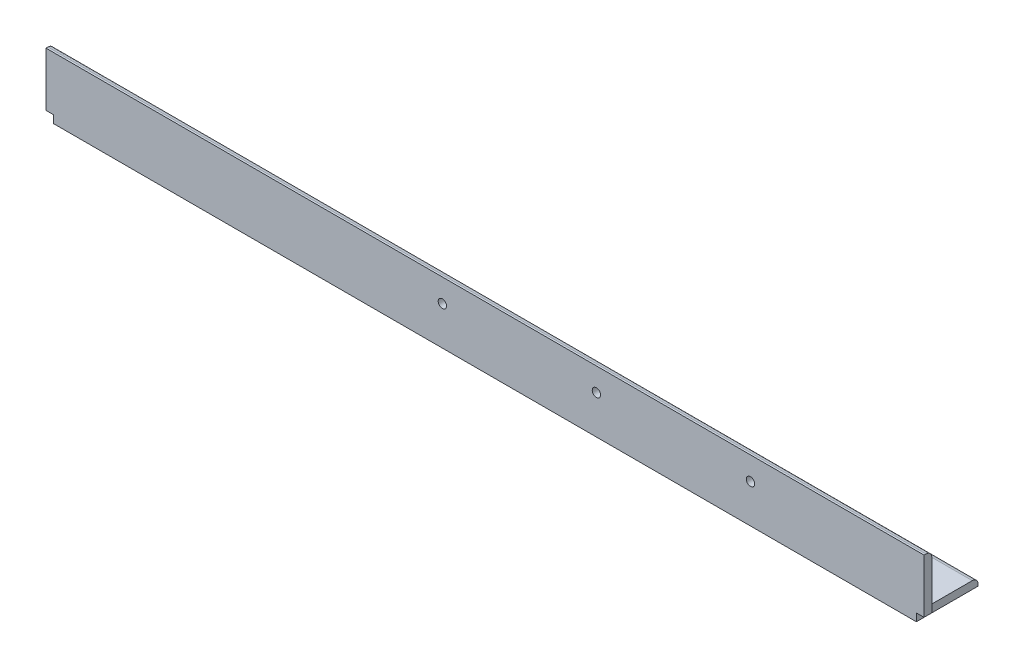
SolidWorks part; units mm, degrees
material "6061-T6 (SS)"
ref_plane "Front Plane" through (0, 0, 0) normal (0, 0, 1) x (1, 0, 0)
ref_plane "Top Plane" through (0, 0, 0) normal (0, 1, 0) x (1, 0, 0)
ref_plane "Right Plane" through (0, 0, 0) normal (1, 0, 0) x (0, 0, -1)
sketch "Sketch1" plane through (0, 0, 0) normal (1, 0, 0) x (0, 0, -1)
  line L0 (0, 0) -> (0, 25.4)
  line L1 (0, 25.4) -> (3.175, 25.4)
  line L2 (3.175, 25.4) -> (3.175, 3.175)
  line L3 (3.175, 3.175) -> (25.4, 3.175)
  line L4 (25.4, 3.175) -> (25.4, 0)
  line L5 (25.4, 0) -> (0, 0)
  dimension "D1" = 25.4
  dimension "D2" = 3.175
extrude "Boss-Extrude1" add sketch "Sketch1" along normal mid plane 361.95
sketch "Sketch3" plane through (0, 0, -25.4) normal (0, 0, -1) x (-1, 0, 0)
  line L0 (-180.975, 0) -> (180.975, 0) construction
  line L1 (-180.975, 3.175) -> (-177.8, 3.175)
  line L2 (-180.975, 3.175) -> (-180.975, 0)
  line L3 (-180.975, 0) -> (-177.8, 0)
  line L4 (-177.8, 3.175) -> (-177.8, 0)
  dimension "D1" = 3.175
extrude "Cut-Extrude2" cut sketch "Sketch3" against normal through all
mirror "Mirror2" about plane through (0, 0, 0) normal (1, 0, 0) of "Cut-Extrude2"
hole_wizard "#8-32 Tapped Hole1" positions "Sketch5" profile "Sketch4" tap size "#8-32" standard "Ansi Inch" end condition up to next
sketch "Sketch5" plane through (0, 0, 0) normal (0, 0, 1) x (1, 0, 0)
  line L0 (180.975, 25.4) -> (-180.975, 25.4) construction
  line L1 (180.975, 25.4) -> (180.975, 3.175) construction
  point P0 (109.4105, 15.875)
  point P1 (45.9105, 15.875)
  point P3 (-17.5895, 15.875)
  dimension "D1" = 9.525
  dimension "D2" = 63.5
  dimension "D3" = 63.5
  dimension "D4" = 71.5645
sketch "Sketch4" plane through (109.4105, 15.875, 0) normal (1, 0, 0) x (0, -1, 0)
  line L0 (0, 0) -> (0, 3.175)
  line L1 (0, 3.175) -> (1.7272, 3.175)
  line L2 (1.7272, 3.175) -> (1.7272, 0)
  line L5 (1.7272, 0) -> (0, 0)
  line L11 (0, -6.35) -> (0, 107.95) construction
  dimension "Thru Tap Drill Dia." = 3.4544
  dimension "Thru Tap Drill Depth" = 3.175
cosmetic thread "Hole Thread1"
cosmetic thread "Hole Thread2"
cosmetic thread "Hole Thread3"
hole_wizard "#8-32 Tapped Hole2" positions "Sketch7" profile "Sketch6" tap size "#8-32" standard "Ansi Inch"
sketch "Sketch7" plane through (0, 3.175, 0) normal (0, 1, 0) x (-1, 0, 0)
  line L0 (-177.8, -3.175) -> (177.8, -3.175) construction
  line L2 (-177.8, -3.175) -> (-177.8, -25.4) construction
  line L3 (177.8, -3.175) -> (177.8, -25.4) construction
  point P0 (131.953, -13.335)
  point P1 (-131.953, -13.335)
  dimension "D1" = 10.16
  dimension "D2" = 45.847
  dimension "D3" = 45.847
sketch "Sketch6" plane through (-131.953, 3.175, -13.335) normal (1, 0, 0) x (0, 0, 1)
  line L0 (0, 0) -> (0, 11.7058)
  line L1 (0, 11.7058) -> (1.7272, 10.668)
  line L2 (1.7272, 10.668) -> (1.7272, 0)
  line L5 (1.7272, 0) -> (0, 0)
  line L10 (0, 11.7058) -> (-1.7272, 10.668) construction
  line L11 (0, -6.35) -> (0, 107.95) construction
  dimension "Tap Drill Dia." = 3.4544
  dimension "Tap Drill Depth" = 10.668
  dimension "Drill Angle" = 118
cosmetic thread "Hole Thread4"
cosmetic thread "Hole Thread5"
fillet "Fillet1" radius 3.175 1 edges at (0, 3.175, -3.175)
fillet "Fillet2" radius 2.3622 2 edges at (0, 25.4, -3.175) (0, 3.175, -25.4)
